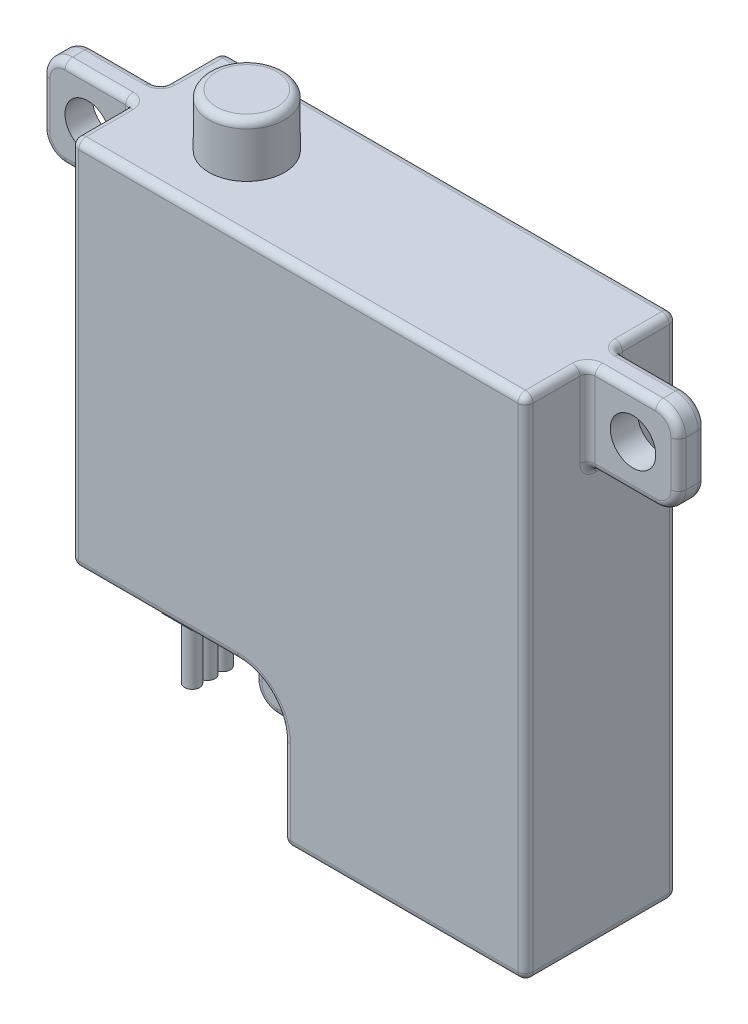
SolidWorks part; units mm, degrees
ref_plane "Front Plane" through (0, 0, 0) normal (0, 0, 1) x (1, 0, 0)
ref_plane "Top Plane" through (0, 0, 0) normal (0, 1, 0) x (1, 0, 0)
ref_plane "Right Plane" through (0, 0, 0) normal (1, 0, 0) x (0, 0, -1)
sketch "Sketch1" plane through (0, 0, 0) normal (0, 0, 1) x (1, 0, 0)
  line L0 (0, 0) -> (16, 0)
  line L1 (16, 0) -> (16, 33.5)
  line L2 (16, 33.5) -> (-14, 33.5)
  line L3 (-14, 33.5) -> (-14, 9)
  line L4 (-14, 9) -> (-3, 9)
  line L5 (0, 0) -> (0, 6)
  arc A0 (-3, 9) -> (0, 6) centre (-3, 6) cw
  dimension "D3" = 3
  dimension "D1" = 30
  dimension "D2" = 33.5
  dimension "D4" = 9
  dimension "D5" = 11
extrude "Boss-Extrude1" add sketch "Sketch1" along normal blind 10
sketch "Sketch2" plane through (-14, 0, 0) normal (-1, 0, 0) x (0, 0, 1)
  line L0 (5, 33.5) -> (5, 9) construction
  line L1 (10, 33.5) -> (0, 33.5) construction
  line L2 (10, 9) -> (0, 9) construction
  line L4 (4.1, 33.5) -> (5.9, 33.5)
  line L5 (4.1, 33.5) -> (4.1, 27.5)
  line L6 (4.1, 27.5) -> (5.9, 27.5)
  line L7 (5.9, 33.5) -> (5.9, 27.5)
  point P11 (5, 33.5)
  dimension "D1" = 1.8
  dimension "D2" = 6
extrude "Boss-Extrude2" add sketch "Sketch2" along normal blind 6
sketch "Sketch3" plane through (16, 0, 0) normal (1, 0, 0) x (0, 0, -1)
  line L0 (-5, 33.5) -> (-5, 0) construction
  line L1 (-10, 33.5) -> (0, 33.5) construction
  line L2 (-10, 0) -> (0, 0) construction
  line L4 (-5.9, 33.5) -> (-4.1, 33.5)
  line L5 (-5.9, 33.5) -> (-5.9, 27.5)
  line L6 (-5.9, 27.5) -> (-4.1, 27.5)
  line L7 (-4.1, 33.5) -> (-4.1, 27.5)
  point P10 (-5, 33.5)
  dimension "D1" = 1.8
  dimension "D2" = 6
extrude "Boss-Extrude3" add sketch "Sketch3" along normal blind 6
sketch "Sketch4" plane through (0, 0, 0) normal (-1, 0, 0) x (0, 0, 1)
  line L0 (5, 0) -> (5, 9) construction
  line L1 (10, 0) -> (0, 0) construction
  line L2 (10, 9) -> (0, 9) construction
  line L4 (4.1, 9) -> (5.9, 9)
  line L5 (4.1, 9) -> (4.1, 3)
  line L6 (4.1, 3) -> (5.9, 3)
  line L7 (5.9, 9) -> (5.9, 3)
  point P10 (5, 9)
  dimension "D1" = 1.8
  dimension "D2" = 6
extrude "Boss-Extrude4" add sketch "Sketch4" along normal blind 6
sketch "Sketch5" plane through (0, 0, 5.9) normal (0, 0, 1) x (1, 0, 0)
  line L0 (-20, 33.5) -> (-14, 33.5) construction
  line L1 (-20, 27.5) -> (-20, 33.5) construction
  line L2 (22, 33.5) -> (16, 33.5) construction
  line L3 (-20, 27.5) -> (-14, 27.5) construction
  line L5 (-6, 3) -> (-6, 9) construction
  line L6 (-6, 3) -> (0, 3) construction
  line L7 (22, 33.5) -> (22, 27.5) construction
  line L8 (22, 27.5) -> (16, 27.5) construction
  line L9 (20.5, 33.5) -> (22, 33.5)
  line L10 (22, 33.5) -> (22, 32)
  line L13 (20.5, 27.5) -> (22, 27.5)
  line L14 (22, 27.5) -> (22, 29)
  line L15 (-6, 4.5) -> (-6, 3)
  line L16 (-6, 3) -> (-4.5, 3)
  circle A0 centre (-17, 30.5) radius 1.5
  circle A1 centre (19, 30.5) radius 1.5
  circle A2 centre (-3, 6) radius 1.5
  arc A3 (-20, 32) -> (-18.5, 33.5) centre (-18.5, 32) cw
  arc A4 (-20, 29) -> (-18.5, 27.5) centre (-18.5, 29) ccw
  arc A5 (-6, 4.5) -> (-4.5, 3) centre (-4.5, 4.5) ccw
  arc A6 (20.5, 33.5) -> (22, 32) centre (20.5, 32) cw
  arc A7 (20.5, 27.5) -> (22, 29) centre (20.5, 29) ccw
  point P10 (-17, 33.5)
  point P14 (-20, 30.5)
  point P17 (19, 33.5)
  line M5 (-14, 33.5) -> (-20, 33.5)
  line M6 (-20, 33.5) -> (-20, 27.5)
  line M7 (-20, 27.5) -> (-14, 27.5)
  dimension "D1" = 3
  dimension "D2" = 1.5
  dimension "D4" = 24.5
  dimension "D5" = 14
extrude "Cut-Extrude2" cut sketch "Sketch5" against normal blind 6 contours A5 L15 L16 | A2 | A4 M6 M7 | A3 M6 M5 | A0 | A1 | L9 A6 L10 | A7 L13 L14
fillet "Fillet1" radius 0.5 63 edges at (-6, 9, 5) (0, 3, 5) (-16.25, 27.5, 5.9) (-19.5607, 27.9393, 5.9) (-20, 30.5, 5.9) (-19.5607, 33.0607, 5.9) (-16.25, 27.5, 4.1) (-19.5607, 27.9393, 4.1) (-20, 30.5, 4.1) (-19.5607, 33.0607, 4.1) (18.25, 27.5, 4.1) (21.5607, 27.9393, 4.1) (22, 30.5, 4.1) (21.5607, 33.0607, 4.1) (18.25, 27.5, 5.9) (21.5607, 27.9393, 5.9) (22, 30.5, 5.9) (21.5607, 33.0607, 5.9) (16, 27.5, 5) (16, 30.5, 4.1) (16, 30.5, 5.9) (-0.8787, 8.1213, 10) (-8.5, 9, 10) (16, 16.75, 10) (0, 3, 10) (-2.25, 3, 4.1) (0, 4.5, 4.1) (-0.8787, 8.1213, 4.1) (-4.5, 9, 4.1) (-6, 6.75, 4.1) (-5.5607, 3.4393, 4.1) (-3, 4.5, 4.1) (-6, 6.75, 5.9) (-4.5, 9, 5.9) (-0.8787, 8.1213, 5.9) (0, 4.5, 5.9) (-2.25, 3, 5.9) (-5.5607, 3.4393, 5.9) (-1.5, 6, 5.9) (-14, 27.5, 5) (-14, 30.5, 5.9) (-14, 21.25, 10) (-14, 9, 5) (-14, 30.5, 4.1) (0, 0, 5) (8, 0, 10) (16, 0, 5) (16, 33.5, 7.95) (1, 33.5, 10) (-14, 33.5, 7.95) (-16.25, 33.5, 5.9) (-16.25, 33.5, 4.1) (-14, 33.5, 2.05) (16, 33.5, 2.05) (18.25, 33.5, 4.1) (18.25, 33.5, 5.9) (8, 0, 0) (16, 16.75, 0) (1, 33.5, 0) (-14, 21.25, 0) (-8.5, 9, 0) (-0.8787, 8.1213, 0) (0, 3, 0)
sketch "Sketch6" plane through (0, 33.5, 0) normal (0, 1, 0) x (1, 0, 0)
  line L0 (-18.5, -5) -> (20.5, -5) construction
  line L1 (-18.5, -4.6) -> (-18.5, -5.4) construction
  line L2 (20.5, -4.6) -> (20.5, -5.4) construction
  line L3 (-14, -3.6) -> (-14, -0.5) construction
  circle A0 centre (-7.4, -5) radius 2.5
  dimension "D1" = 5
  dimension "D2" = 6.6
extrude "Boss-Extrude5" add sketch "Sketch6" along normal blind 3.5
fillet "Fillet2" radius 0.5 1 edges at (-9.9, 37, 5)
sketch "Sketch7" plane through (0, 9, 0) normal (0, -1, 0) x (1, 0, 0)
  line L1 (-11.5, 7.5) -> (-8.5, 7.5)
  line L2 (-11.5, 7.5) -> (-11.5, 2.5)
  line L3 (-11.5, 2.5) -> (-8.5, 2.5)
  line L4 (-8.5, 7.5) -> (-8.5, 2.5)
  line L5 (-13.5, 10) -> (-3, 10) construction
  line L6 (-14, 0.5) -> (-14, 9.5) construction
  dimension "D1" = 3
  dimension "D2" = 5
  dimension "D3" = 2.5
  dimension "D4" = 2.5
extrude "Boss-Extrude6" add sketch "Sketch7" along normal blind 0.75
sketch "Sketch9" plane through (0, 8.25, 0) normal (0, -1, 0) x (1, 0, 0)
  line L0 (-11.5, 7.5) -> (-11.5, 2.5) construction
  line L1 (-11, 3) -> (-9, 3)
  line L2 (-11, 3) -> (-11, 7)
  line L3 (-11, 7) -> (-9, 7)
  line L4 (-9, 3) -> (-9, 7)
  line L5 (-8.5, 7.5) -> (-11.5, 7.5) construction
  dimension "D1" = 2
  dimension "D2" = 4
  dimension "D3" = 0.5
  dimension "D4" = 0.5
extrude "Boss-Extrude7" add sketch "Sketch9" along normal blind 2
sketch "Sketch11" plane through (0, 6.25, 0) normal (0, -1, 0) x (1, 0, 0)
  line L0 (-11, 3) -> (-9, 3) construction
  line L1 (-11, 7) -> (-11, 3) construction
  circle A0 centre (-10, 6.01) radius 0.5
  circle A1 centre (-10, 5) radius 0.5
  circle A2 centre (-10, 3.99) radius 0.5
  dimension "D1" = 1
  dimension "D2" = 1
  dimension "D3" = 1
  dimension "D4" = 2
  dimension "D5" = 1.01
  dimension "D6" = 1.01
  dimension "D7" = 1
extrude "Boss-Extrude8" add sketch "Sketch11" along normal blind 4
